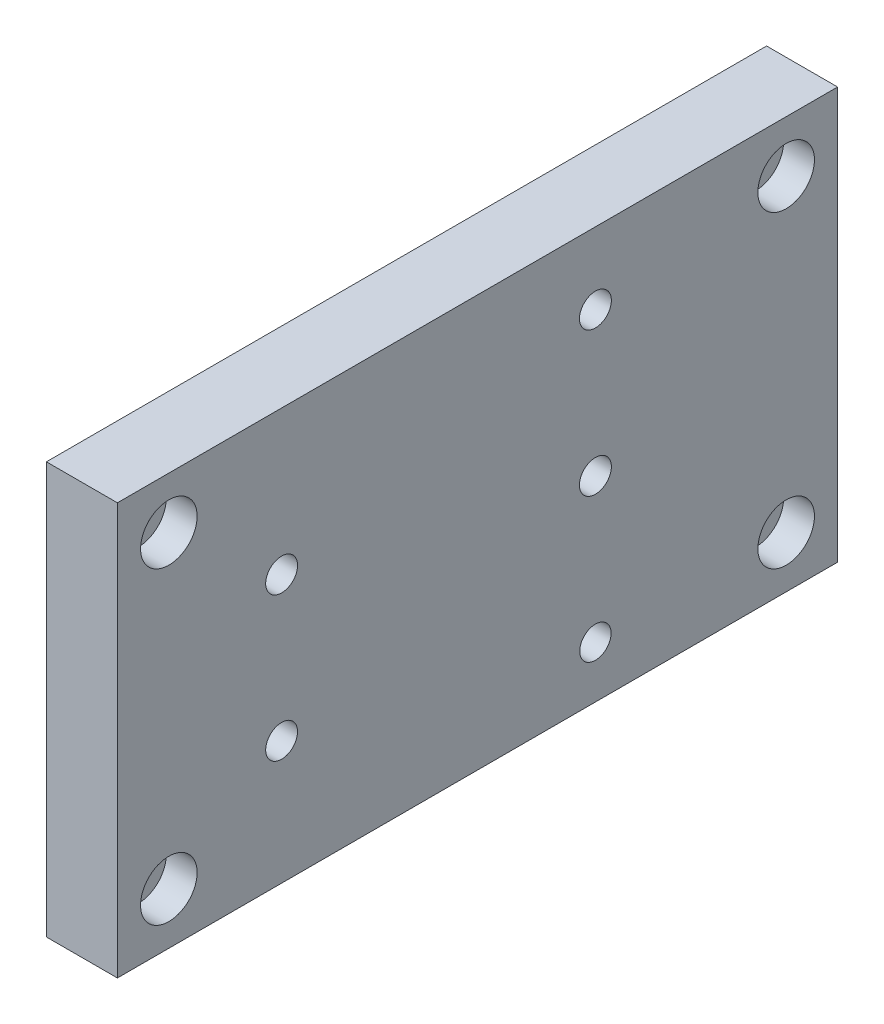
SolidWorks part; units mm, degrees
ref_plane "前视基准面" through (0, 0, 0) normal (0, 0, 1) x (1, 0, 0)
ref_plane "上视基准面" through (0, 0, 0) normal (0, 1, 0) x (1, 0, 0)
ref_plane "右视基准面" through (0, 0, 0) normal (1, 0, 0) x (0, 0, -1)
other "Configuration Table"
sketch "草图1" plane through (0, 0, 0) normal (1, 0, 0) x (0, 0, -1)
  line L1 (0, 0) -> (70, 0)
  line L2 (0, 0) -> (0, 40)
  line L3 (0, 40) -> (70, 40)
  line L4 (70, 0) -> (70, 40)
  dimension "D1" = 40
  dimension "D2" = 70
extrude "凸台-拉伸3" add sketch "草图1" along normal blind 6.9
sketch "草图2" plane through (6.9, 0, 0) normal (1, 0, 0) x (0, 0, -1)
  line L0 (-1000, 20) -> (49000, 20) construction
  line L1 (0, 40) -> (5, 40)
  line L2 (0, 40) -> (0, 35)
  line L3 (0, 35) -> (5, 35)
  line L4 (5, 40) -> (5, 35)
  line L5 (0, 40) -> (0, 0) construction
  line L6 (35, -960) -> (35, 49040) construction
  line L7 (70, 40) -> (0, 40) construction
  circle A0 centre (5, 35) radius 1.5
  circle A1 centre (5, 5) radius 1.5
  circle A2 centre (65, 35) radius 1.5
  circle A3 centre (65, 5) radius 1.5
  point P11 (0, 20)
  point P16 (35, 40)
  dimension "D3" = 3
  dimension "D1" = 5
  dimension "D2" = 5
extrude "切除-拉伸1" cut sketch "草图2" against normal blind 6.9 contours L3 A0 L4 | L4 A0 L3 | A1 | A3 | A2
sketch "草图5" plane through (6.9, 0, 0) normal (1, 0, 0) x (0, 0, -1)
  circle A0 centre (5, 35) radius 2.75
  circle A1 centre (5, 5) radius 2.75
  circle A2 centre (65, 35) radius 2.75
  circle A3 centre (65, 5) radius 2.75
  dimension "D1" = 5.5
  dimension "D2" = 5.5
  dimension "D3" = 5.5
  dimension "D4" = 5.5
extrude "切除-拉伸3" cut sketch "草图5" against normal blind 3
sketch "草图6" plane through (6.9, 0, 0) normal (1, 0, 0) x (0, 0, -1)
  circle A0 centre (46.4611, 5.0356) radius 1.5248
  circle A1 centre (46.4611, 19.0356) radius 1.55
  circle A2 centre (46.4611, 33.0356) radius 1.55
  circle A3 centre (15.9611, 25.9856) radius 1.55
  circle A4 centre (15.9611, 11.9856) radius 1.55
extrude "切除-拉伸4" cut sketch "草图6" against normal blind 10
sketch "草图7" plane through (0, 0, 0) normal (-1, 0, 0) x (0, 0, 1)
  circle A0 centre (-46.4611, 33.0356) radius 3
  circle A1 centre (-46.4611, 19.0356) radius 3
  circle A2 centre (-46.4611, 5.0356) radius 3
  circle A3 centre (-15.9611, 11.9856) radius 3
  circle A4 centre (-15.9611, 25.9856) radius 3
  dimension "D1" = 6
  dimension "D2" = 6
  dimension "D3" = 6
  dimension "D4" = 6
  dimension "D5" = 6
extrude "切除-拉伸6" cut sketch "草图7" against normal blind 3
